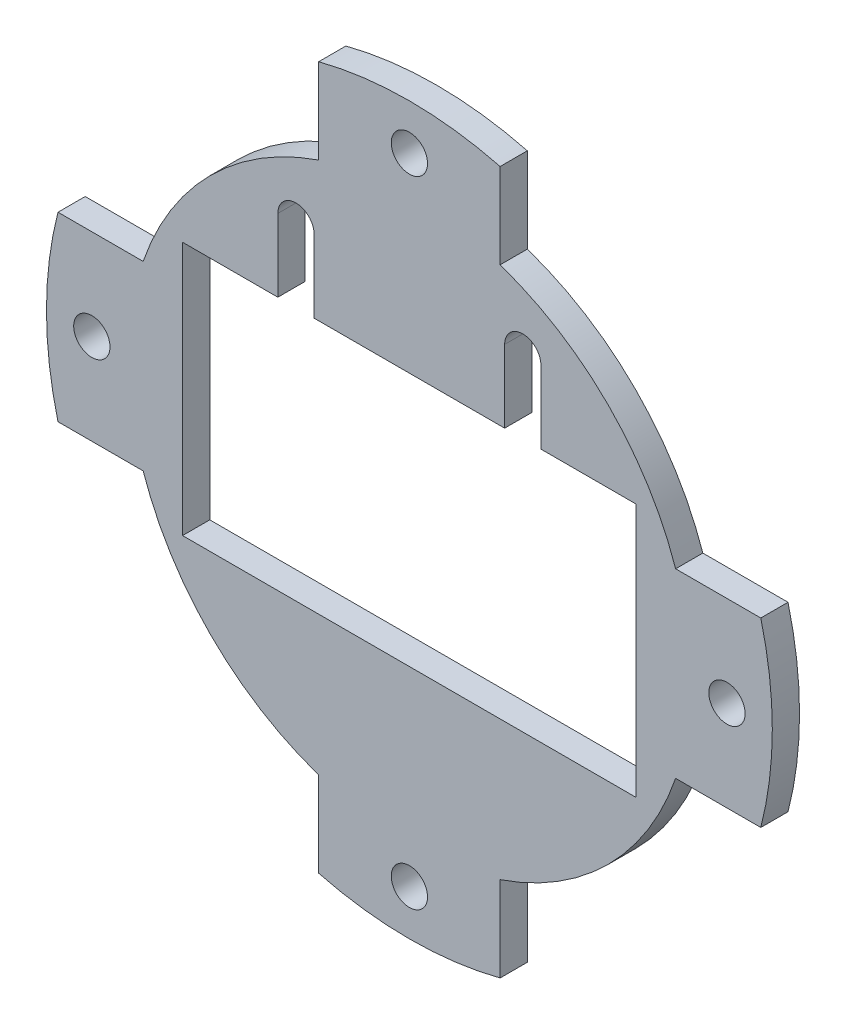
SolidWorks part; units mm, degrees
ref_plane "Front Plane" through (0, 0, 0) normal (0, 0, 1) x (1, 0, 0)
ref_plane "Top Plane" through (0, 0, 0) normal (0, 1, 0) x (1, 0, 0)
ref_plane "Right Plane" through (0, 0, 0) normal (1, 0, 0) x (0, 0, -1)
sketch "Sketch1" plane through (0, 0, 0) normal (0, 0, 1) x (1, 0, 0)
  line L0 (0, 31) -> (0, 40) construction
  line L1 (10, 29.3428) -> (10, 38.7298)
  line L2 (-10, 29.3428) -> (-10, 38.7298)
  line L5 (10, 0) -> (10, 40) construction
  line L6 (0, 0) -> (0, 40) construction
  line L7 (-10, 0) -> (-10, 40) construction
  line L8 (29.3428, 10) -> (38.7298, 10)
  line L9 (29.3428, -10) -> (38.7298, -10)
  line L10 (10, -29.3428) -> (10, -38.7298)
  line L11 (-10, -29.3428) -> (-10, -38.7298)
  line L12 (-29.3428, -10) -> (-38.7298, -10)
  line L13 (-29.3428, 10) -> (-38.7298, 10)
  arc A0 (10, 38.7298) -> (-10, 38.7298) centre (0, 0) ccw
  arc A2 (-10, 29.3428) -> (-29.3428, 10) centre (0, 0) ccw
  arc A3 (38.7298, -10) -> (38.7298, 10) centre (0, 0) ccw
  arc A4 (-10, -38.7298) -> (10, -38.7298) centre (0, 0) ccw
  arc A5 (-38.7298, 10) -> (-38.7298, -10) centre (0, 0) ccw
  arc A6 (-29.3428, -10) -> (-10, -29.3428) centre (0, 0) ccw
  arc A7 (29.3428, 10) -> (10, 29.3428) centre (0, 0) ccw
  arc A8 (10, -29.3428) -> (29.3428, -10) centre (0, 0) ccw
  point P27 (0, 0)
  dimension "D1" = 80
  dimension "D3" = 10
  dimension "D4" = 10
extrude "Boss-Extrude1" add sketch "Sketch1" along normal blind 3
sketch "Sketch2" plane through (0, 0, 3) normal (0, 0, 1) x (1, 0, 0)
  line L1 (25, 14) -> (-25, 14)
  line L2 (25, 14) -> (25, -14)
  line L3 (25, -14) -> (-25, -14)
  line L4 (-25, 14) -> (-25, -14)
  line L5 (25, 14) -> (-25, -14) construction
  line L6 (25, -14) -> (-25, 14) construction
  point P0 (0, 0)
  dimension "D1" = 50
  dimension "D2" = 28
extrude "Cut-Extrude1" cut sketch "Sketch2" against normal up to next
sketch "Sketch3" plane through (0, 0, 3) normal (0, 0, 1) x (1, 0, 0)
  line L0 (0, 0) -> (0, 40) construction
  line L1 (4.9006, 22) -> (-14.3438, 22) construction
  line L2 (25, 14) -> (-25, 14) construction
  line L3 (-10.5, 22) -> (-10.5, 14)
  line L4 (10.5, 22) -> (10.5, 14)
  line L5 (-14.5, 22) -> (-14.5, 14)
  line L6 (14.5, 22) -> (14.5, 14)
  line L7 (14.5, 14) -> (10.5, 14)
  line L8 (-14.5, 14) -> (-10.5, 14)
  arc A0 (10, 38.7298) -> (-10, 38.7298) centre (0, 0) ccw construction
  arc A1 (-10.5, 22) -> (-14.5, 22) centre (-12.5, 22) ccw
  arc A2 (10.5, 22) -> (14.5, 22) centre (12.5, 22) cw
  dimension "D1" = 25
  dimension "D2" = 4
  dimension "D3" = 8
extrude "Cut-Extrude2" cut sketch "Sketch3" against normal up to next
sketch "Sketch4" plane through (0, 0, 3) normal (0, 0, 1) x (1, 0, 0)
  line L0 (0, 0) -> (0, 40) construction
  arc A0 (10, 38.7298) -> (-10, 38.7298) centre (0, 0) ccw construction
  circle A1 centre (0, 35) radius 2
  circle A2 centre (35, 0) radius 2
  circle A3 centre (0, -35) radius 2
  circle A4 centre (-35, 0) radius 2
  point P17 (0, 0)
  dimension "D1" = 35
  dimension "D2" = 4
extrude "Cut-Extrude3" cut sketch "Sketch4" against normal blind 10
